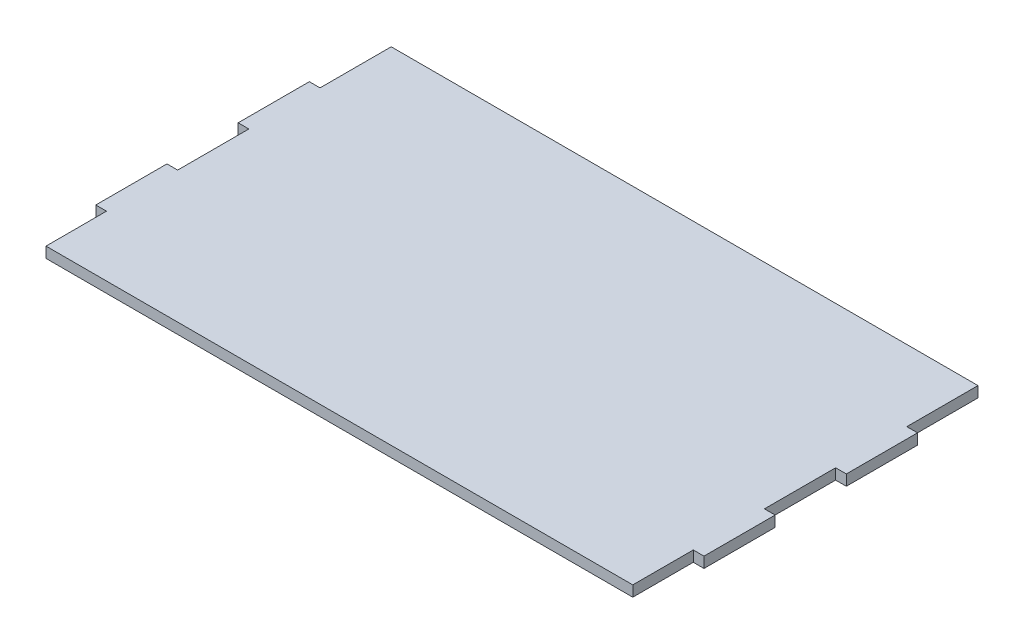
SolidWorks part; units mm, degrees
ref_plane "Ön Düzlem" through (0, 0, 0) normal (0, 0, 1) x (1, 0, 0)
ref_plane "Üst Düzlem" through (0, 0, 0) normal (0, 1, 0) x (1, 0, 0)
ref_plane "Sağ Düzlem" through (0, 0, 0) normal (1, 0, 0) x (0, 0, -1)
sketch "Sketch2" plane through (0, 0, 0) normal (0, 1, 0) x (1, 0, 0)
  line L0 (-76.7, -26.931) -> (-76.7, -8.977)
  line L3 (74, 44.885) -> (-74, 44.885)
  line L8 (-76.7, 8.977) -> (-76.7, 26.931)
  line L10 (-76.7, 26.931) -> (-74, 26.931)
  line L11 (-74, 8.977) -> (-74, -8.977)
  line L12 (-74, 26.931) -> (-74, 44.885)
  line L13 (-76.7, 8.977) -> (-74, 8.977)
  line L14 (-76.7, -26.931) -> (-74, -26.931)
  line L15 (-76.7, -8.977) -> (-74, -8.977)
  line L16 (-74, -26.931) -> (-74, -42.185)
  line L17 (76.7, -26.931) -> (76.7, -8.977)
  line L19 (76.7, 8.977) -> (76.7, 26.931)
  line L21 (74, -26.931) -> (74, -42.185)
  line L22 (74, 44.885) -> (74, 26.931)
  line L23 (76.7, -26.931) -> (74, -26.931)
  line L24 (76.7, -8.977) -> (74, -8.977)
  line L25 (76.7, 8.977) -> (74, 8.977)
  line L26 (76.7, 26.931) -> (74, 26.931)
  line L27 (74, 8.977) -> (74, -8.977)
  line L29 (-74, -42.185) -> (74, -42.185)
  point P0 (0, 0)
extrude "Boss-Extrude1" add sketch "Sketch2" along normal blind 2.7
